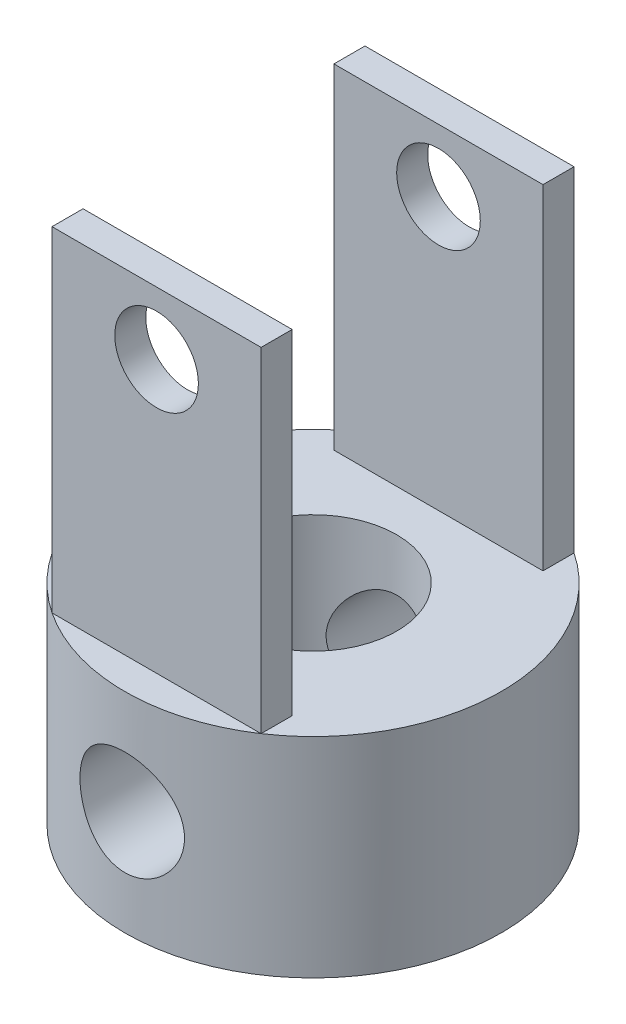
SolidWorks part; units mm, degrees
ref_plane "Front Plane" through (0, 0, 0) normal (0, 0, 1) x (1, 0, 0)
ref_plane "Top Plane" through (0, 0, 0) normal (0, 1, 0) x (1, 0, 0)
ref_plane "Right Plane" through (0, 0, 0) normal (1, 0, 0) x (0, 0, -1)
sketch "Sketch2" plane through (0, 0, 0) normal (0, 1, 0) x (1, 0, 0)
  circle A0 centre (0, 0) radius 4.5
  dimension "D1" = 9
extrude "Boss-Extrude1" add sketch "Sketch2" along normal blind 5
sketch "Sketch3" plane through (0, 5, 0) normal (0, 1, 0) x (1, 0, 0)
  line L0 (-4.5, 0) -> (4.5, 0) construction
  line L1 (-2.5, -3) -> (2.5, -3)
  line L2 (-2.5, 3.7417) -> (2.5, 3.7417)
  line L3 (-2.5, 3.7417) -> (-2.5, 3)
  line L4 (-2.5, 3) -> (2.5, 3)
  line L5 (2.5, 3.7417) -> (2.5, 3)
  line L6 (2.5, -3.7417) -> (2.5, -3)
  line L7 (-2.5, -3.7417) -> (2.5, -3.7417)
  line L8 (-2.5, -3.7417) -> (-2.5, -3)
  circle A0 centre (0, 0) radius 4.5 construction
  dimension "D1" = 3
  dimension "D2" = 5
extrude "Boss-Extrude2" add sketch "Sketch3" along normal blind 8
sketch "Sketch4" plane through (0, 0, 3.7417) normal (0, 0, 1) x (1, 0, 0)
  line L0 (0, 0) -> (0, 13) construction
  line L1 (-2.5, 13) -> (2.5, 13) construction
  line L2 (-4.5, 0) -> (4.5, 0) construction
  circle A0 centre (0, 11.5) radius 1
  dimension "D2" = 2
  dimension "D1" = 11.5
extrude "Cut-Extrude1" cut sketch "Sketch4" against normal up to surface (7.4833 mm away) up to face at (0, 9, -3.7417)
sketch "Sketch6" plane through (0, 0, 0) normal (0, -1, 0) x (1, 0, 0)
  circle A0 centre (0, 0) radius 2
  dimension "D1" = 4
extrude "Cut-Extrude2" cut sketch "Sketch6" against normal up to surface (5 mm away) up to face at (0, 5, 0)
ref_plane "Plane1" through (0, 0, 0) normal (0, 0, 1) x (1, 0, 0)
ref_plane "Plane2" through (0, 0, 4.5) normal (0, 0, 1) x (1, 0, 0)
sketch "Sketch8" plane through (0, 0, 4.5) normal (0, 0, 1) x (1, 0, 0)
  line L0 (0, 0) -> (0, 4) construction
  line L1 (-4.5, 0) -> (4.5, 0) construction
  line L2 (-4, 2.5) -> (4, 2.5) construction
  point P6 (0, 2.5)
  point P9 (-3.9818, 2.5)
  dimension "D1" = 2.5
  dimension "D2" = 4
  dimension "D3" = 8
  dimension "D4" = 4
hole_wizard "M3x0.5 Tapped Hole2" positions "Sketch8" profile "Sketch9" tap size "M3x0.5" standard "ANSI Metric"
sketch "Sketch9" plane through (0, 2.5, 4.5) normal (1, 0, 0) x (0, -1, 0)
  line L0 (0, 0) -> (0, 4.499)
  line L1 (0, 4.499) -> (1.25, 3.7479)
  line L2 (1.25, 3.7479) -> (1.25, 0)
  line L5 (1.25, 0) -> (0, 0)
  line L10 (0, 4.499) -> (-1.25, 3.7479) construction
  line L11 (0, -6.35) -> (0, 107.95) construction
  dimension "Tap Drill Dia." = 2.5
  dimension "Tap Drill Depth" = 4.499
  dimension "Drill Angle" = 118
cosmetic thread "Hole Thread2" parameters "D1"=6, "D2"=3
mirror "Mirror1" about plane through (0, 0, 0) normal (0, 0, 1) of "M3x0.5 Tapped Hole2"
cosmetic thread "Hole Thread3" parameters "D1"=6, "D2"=3
